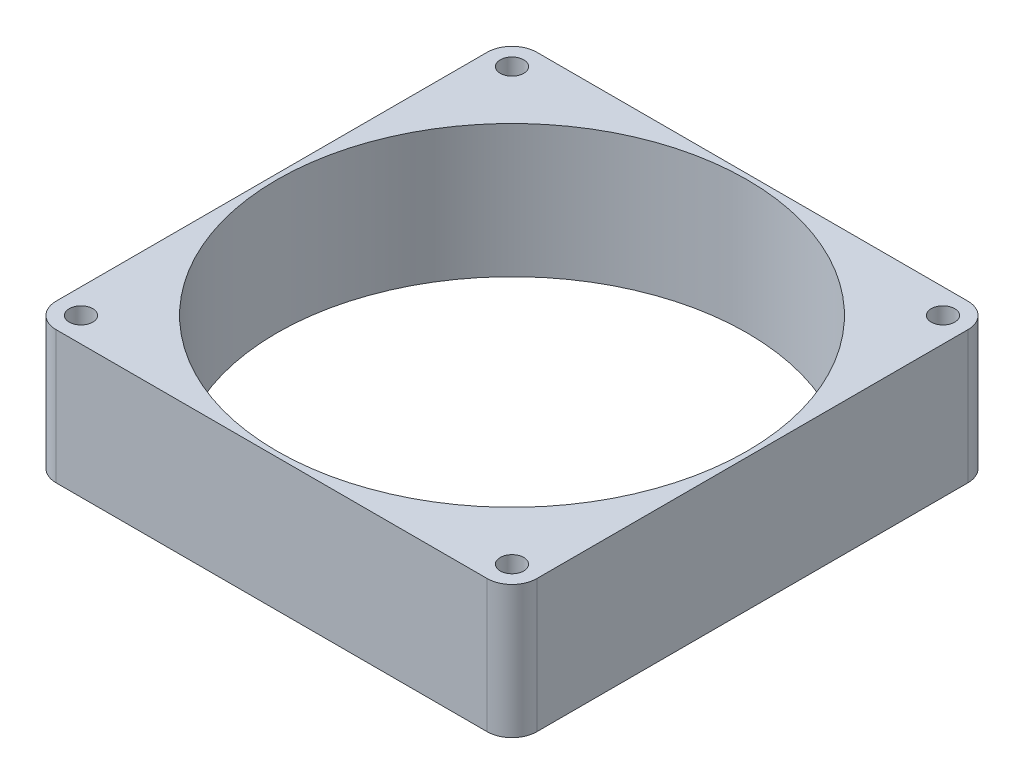
SolidWorks part; units mm, degrees
ref_plane "Front Plane" through (0, 0, 0) normal (0, 0, 1) x (1, 0, 0)
ref_plane "Top Plane" through (0, 0, 0) normal (0, 1, 0) x (1, 0, 0)
ref_plane "Right Plane" through (0, 0, 0) normal (1, 0, 0) x (0, 0, -1)
sketch "Sketch1" plane through (0, 0, 0) normal (0, 1, 0) x (1, 0, 0)
  line L0 (0, -55) -> (0, 55) construction
  line L1 (-41.25, -46) -> (41.25, -46)
  line L2 (-46, -41.25) -> (-46, 41.25)
  line L3 (-41.25, 46) -> (41.25, 46)
  line L4 (46, -41.25) -> (46, 41.25)
  line L5 (-46, -46) -> (46, 46) construction
  line L6 (-46, 46) -> (46, -46) construction
  line L7 (-55, 0) -> (55, 0) construction
  circle A0 centre (0, 0) radius 45
  circle A1 centre (-41.25, 41.25) radius 2.25
  circle A2 centre (41.25, 41.25) radius 2.25
  circle A3 centre (41.25, -41.25) radius 2.25
  circle A4 centre (-41.25, -41.25) radius 2.25
  arc A5 (41.25, 46) -> (46, 41.25) centre (41.25, 41.25) cw
  arc A6 (41.25, -46) -> (46, -41.25) centre (41.25, -41.25) ccw
  arc A7 (-41.25, -46) -> (-46, -41.25) centre (-41.25, -41.25) cw
  arc A8 (-46, 41.25) -> (-41.25, 46) centre (-41.25, 41.25) cw
  point P0 (0, 0)
  dimension "D3" = 90
  dimension "D6" = 4.5
  dimension "D7" = 4.75
  dimension "D1" = 92
  dimension "D2" = 92
  dimension "D4" = 41.25
  dimension "D5" = 41.25
extrude "Boss-Extrude1" add sketch "Sketch1" along normal blind 25.4
